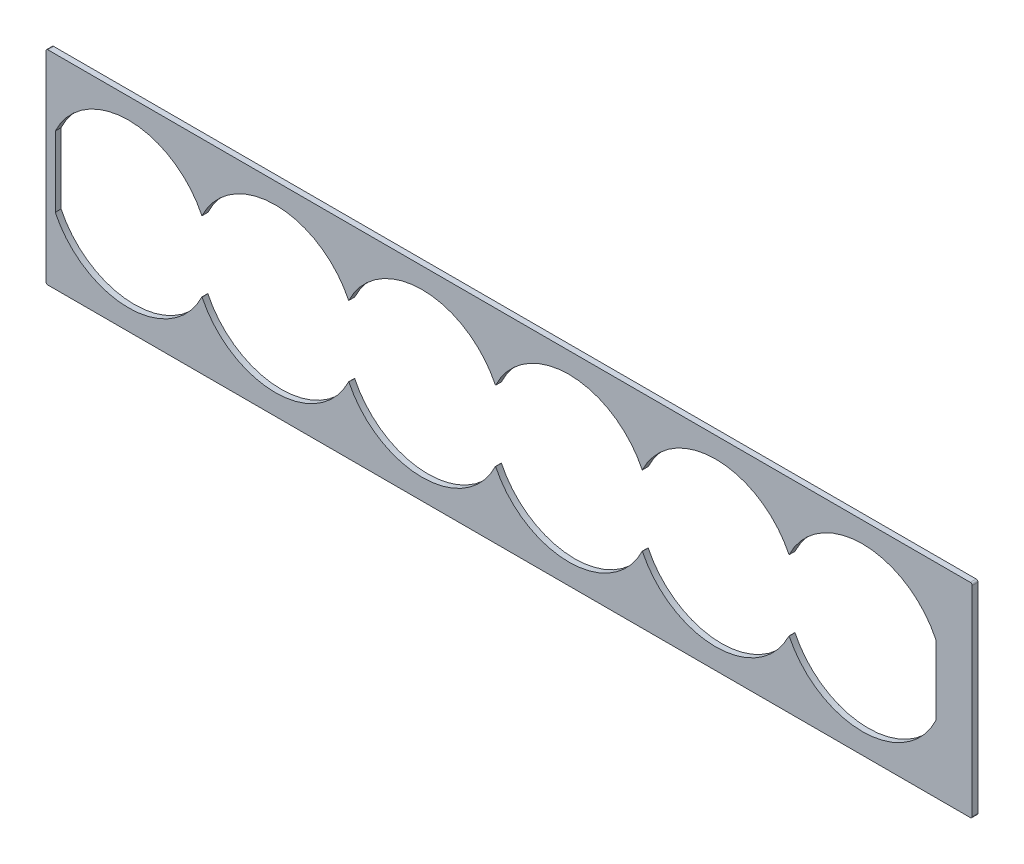
SolidWorks part; units mm, degrees
material "Silicon"
ref_plane "Front" through (0, 0, 0) normal (0, 0, 1) x (1, 0, 0)
ref_plane "Top" through (0, 0, 0) normal (0, 1, 0) x (1, 0, 0)
ref_plane "Right" through (0, 0, 0) normal (1, 0, 0) x (0, 0, -1)
sketch "Sketch4" plane through (0, 0, 0) normal (0, 0, 1) x (1, 0, 0)
  line L0 (317.5, 0) -> (317.5, 139.7) construction
  line L1 (207.493, 93.9963) -> (207.493, 45.7037) construction
  line L2 (0, 0) -> (635, 0)
  line L3 (317.5, 69.85) -> (56.604, 69.85) construction
  line L4 (6.35, 93.9963) -> (6.35, 45.7037)
  line L5 (106.858, 93.9963) -> (106.858, 45.7037) construction
  line L6 (0, 0) -> (0, 139.7)
  line L7 (0, 139.7) -> (635, 139.7)
  line L8 (635, 0) -> (635, 139.7)
  line L9 (106.985, 93.9963) -> (106.985, 45.7037) construction
  line L10 (308.128, 93.9963) -> (308.128, 45.7037) construction
  line L11 (207.62, 93.9963) -> (207.62, 45.7037) construction
  line L12 (106.858, 93.9963) -> (106.985, 93.9963)
  line L13 (207.493, 93.9963) -> (207.62, 93.9963)
  line L14 (207.62, 45.7037) -> (207.493, 45.7037)
  line L15 (106.985, 45.7037) -> (106.858, 45.7037)
  line L16 (408.763, 93.9963) -> (408.763, 45.7037) construction
  line L17 (308.255, 93.9963) -> (308.255, 45.7037) construction
  line L18 (509.398, 93.9963) -> (509.398, 45.7037) construction
  line L19 (408.89, 93.9963) -> (408.89, 45.7037) construction
  line L20 (610.033, 93.9963) -> (610.033, 45.7037)
  line L21 (509.525, 93.9963) -> (509.525, 45.7037) construction
  line L22 (509.398, 93.9963) -> (509.525, 93.9963)
  line L23 (509.398, 45.7037) -> (509.525, 45.7037)
  line L24 (408.763, 45.7037) -> (408.89, 45.7037)
  line L25 (408.763, 93.9963) -> (408.89, 93.9963)
  line L26 (308.128, 93.9963) -> (308.255, 93.9963)
  line L27 (308.128, 45.7037) -> (308.255, 45.7037)
  arc A0 (6.35, 45.7037) -> (106.858, 45.7037) centre (56.604, 69.85) ccw
  arc A1 (106.858, 93.9963) -> (6.35, 93.9963) centre (56.604, 69.85) ccw
  arc A2 (106.985, 45.7037) -> (207.493, 45.7037) centre (157.239, 69.85) ccw
  arc A3 (207.493, 93.9963) -> (106.985, 93.9963) centre (157.239, 69.85) ccw
  arc A4 (207.62, 45.7037) -> (308.128, 45.7037) centre (257.874, 69.85) ccw
  arc A5 (308.128, 93.9963) -> (207.62, 93.9963) centre (257.874, 69.85) ccw
  arc A6 (308.255, 45.7037) -> (408.763, 45.7037) centre (358.509, 69.85) ccw
  arc A7 (408.763, 93.9963) -> (308.255, 93.9963) centre (358.509, 69.85) ccw
  arc A8 (408.89, 45.7037) -> (509.398, 45.7037) centre (459.144, 69.85) ccw
  arc A9 (509.398, 93.9963) -> (408.89, 93.9963) centre (459.144, 69.85) ccw
  arc A10 (509.525, 45.7037) -> (610.033, 45.7037) centre (559.779, 69.85) ccw
  arc A11 (610.033, 93.9963) -> (509.525, 93.9963) centre (559.779, 69.85) ccw
  point P8 (317.5, 69.85)
  dimension "D2" = 111.508
  dimension "D1" = 100.508
  dimension "D3" = 139.7
  dimension "D4" = 635
  dimension "D6" = 6.35
  dimension "D7" = 0.127
  dimension "D5" = 6
extrude "DIMENSIONS CONTROL OPTICS LOCATION" add sketch "Sketch4" along normal blind 4
fillet "Fillet1" radius 1.27 4 edges at (635, 139.7, 2) (0, 0, 2) (0, 139.7, 2) (635, 0, 2)
